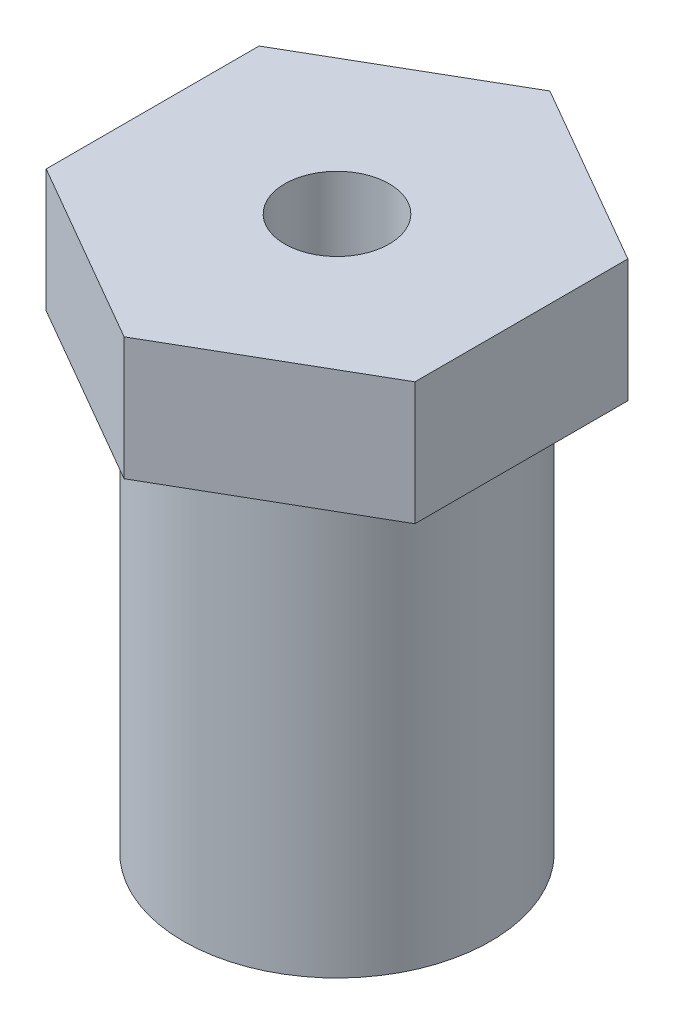
SolidWorks part; units mm, degrees
material "Brass"
ref_plane "Front Plane" through (0, 0, 0) normal (0, 0, 1) x (1, 0, 0)
ref_plane "Top Plane" through (0, 0, 0) normal (0, 1, 0) x (1, 0, 0)
ref_plane "Right Plane" through (0, 0, 0) normal (1, 0, 0) x (0, 0, -1)
sketch "Sketch1" plane through (0, 0, 0) normal (0, 1, 0) x (1, 0, 0)
  circle A0 centre (0, 0) radius 5
  circle A1 centre (0, 0) radius 3
  dimension "D1" = 6
  dimension "D2" = 10
extrude "Boss-Extrude1" add sketch "Sketch1" along normal blind 14
sketch "Sketch2" plane through (0, 14, 0) normal (0, 1, 0) x (1, 0, 0)
  line L1 (0, 6.9282) -> (-6, 3.4641)
  line L2 (-6, 3.4641) -> (-6, -3.4641)
  line L3 (-6, -3.4641) -> (0, -6.9282)
  line L4 (0, -6.9282) -> (6, -3.4641)
  line L5 (6, -3.4641) -> (6, 3.4641)
  line L6 (6, 3.4641) -> (0, 6.9282)
  circle A0 centre (0, 0) radius 6 construction
  dimension "D1" = 12
extrude "Boss-Extrude2" add sketch "Sketch2" along normal blind 4
hole_wizard "M3 Clearance Hole1" positions "Sketch4" profile "Sketch5" hole size "M3" standard "ISO" end condition up to next
sketch "Sketch4" plane through (0, 18, 0) normal (0, 1, 0) x (1, 0, 0)
  point P0 (0, 0)
sketch "Sketch5" plane through (0, 18, 0) normal (1, 0, 0) x (0, 0, 1)
  line L0 (0, 0) -> (0, 4)
  line L1 (0, 4) -> (1.7, 4)
  line L2 (1.7, 4) -> (1.7, 0)
  line L5 (1.7, 0) -> (0, 0)
  line L11 (0, -6.35) -> (0, 107.95) construction
  dimension "Thru Hole Dia." = 3.4
  dimension "Thru Hole Depth" = 4
sketch "Sketch6" plane through (-3, 0, -5.1962) normal (-0.5, 0, -0.866) x (-0.866, 0, 0.5)
  line L1 (-5, 14) -> (-5, 0) construction
  line L2 (-5, 14) -> (-5, 0) construction
  circle A0 centre (0, 6) radius 1.5
  point P7 (0, 6)
  dimension "D2" = 3
  dimension "D1" = 6
hole_wizard "M3 Clearance Hole2" positions "Sketch7" profile "Sketch8" hole size "M3" standard "ISO"
sketch "Sketch7" plane through (-3, 0, -5.1962) normal (-0.5, 0, -0.866) x (-0.866, 0, 0.5)
  point P0 (0, 6)
sketch "Sketch8" plane through (-3, 6, -5.1962) normal (0, 1, 0) x (-0.866, 0, 0.5)
  line L0 (0, 0) -> (0, 3)
  line L1 (0, 3) -> (1.7, 3)
  line L2 (1.7, 3) -> (1.7, 0)
  line L5 (1.7, 0) -> (0, 0)
  line L11 (0, -6.35) -> (0, 107.95) construction
  dimension "Thru Hole Dia." = 3.4
  dimension "Thru Hole Depth" = 3
thread "Thread1" pitch 0.3175 start angle 0, offset 0, length 0, pitch 0.3175, diameter 3.4
ref_plane "Plane1" through (-1.7, 18, 0) normal (0, 0, 1) x (-1, 0, 0)
sketch "Thread Profile1" plane through (-1.7, 18, 0) normal (0, 0, 1) x (-1, 0, 0)
  line L0 (0, 0) -> (0, 0.3175) construction
  line L11 (0, 0) -> (0, 0.2778)
  line L12 (0, 0.2778) -> (-0.1719, 0.1786)
  line L13 (-0.1719, 0.1786) -> (-0.1719, 0.0992)
  line L15 (-0.1719, 0.0992) -> (0, 0)
  line L17 (-0.1719, 0.1389) -> (0, 0.1389) construction
  point P2 (0, 0)
  dimension "Pitch" = 0.3175
  dimension "Profile_Angle" = 60
  dimension "Profile_Land" = 0.0794
  dimension "Profile_Height" = 0.1719
sketch "Sketch11" plane through (-3, 0, -5.1962) normal (-0.5, 0, -0.866) x (-0.866, 0, 0.5)
  circle A0 centre (0, 6) radius 1.7 construction
  circle A1 centre (0, 6) radius 1.7
  circle A2 centre (0, 6) radius 2.5494
extrude "Boss-Extrude3" add sketch "Sketch11" against normal up to surface (1.2979 mm away)
thread "Thread2" pitch 0.3175 start angle 0, offset 0, length 3, pitch 0.3175, diameter 3.4
ref_plane "Plane2" through (-1.5278, 6, -6.0462) normal (0, -1, 0) x (0.866, 0, -0.5)
sketch "Thread Profile2" plane through (-1.5278, 6, -6.0462) normal (0, -1, 0) x (0.866, 0, -0.5)
  line L0 (0, 0) -> (0, 0.3175) construction
  line L11 (0, 0) -> (0, 0.2778)
  line L12 (0, 0.2778) -> (-0.1719, 0.1786)
  line L13 (-0.1719, 0.1786) -> (-0.1719, 0.0992)
  line L15 (-0.1719, 0.0992) -> (0, 0)
  line L17 (-0.1719, 0.1389) -> (0, 0.1389) construction
  point P2 (0, 0)
  dimension "Pitch" = 0.3175
  dimension "Profile_Angle" = 60
  dimension "Profile_Land" = 0.0794
  dimension "Profile_Height" = 0.1719
sketch "Sketch14" plane through (-3, 0, -5.1962) normal (-0.5, 0, -0.866) x (-0.866, 0, 0.5)
  circle A0 centre (0, 6) radius 2.5494 construction
  circle A1 centre (0, 6) radius 2.5494
extrude "Cut-Extrude2" cut sketch "Sketch14" against normal blind 1 contours A1
